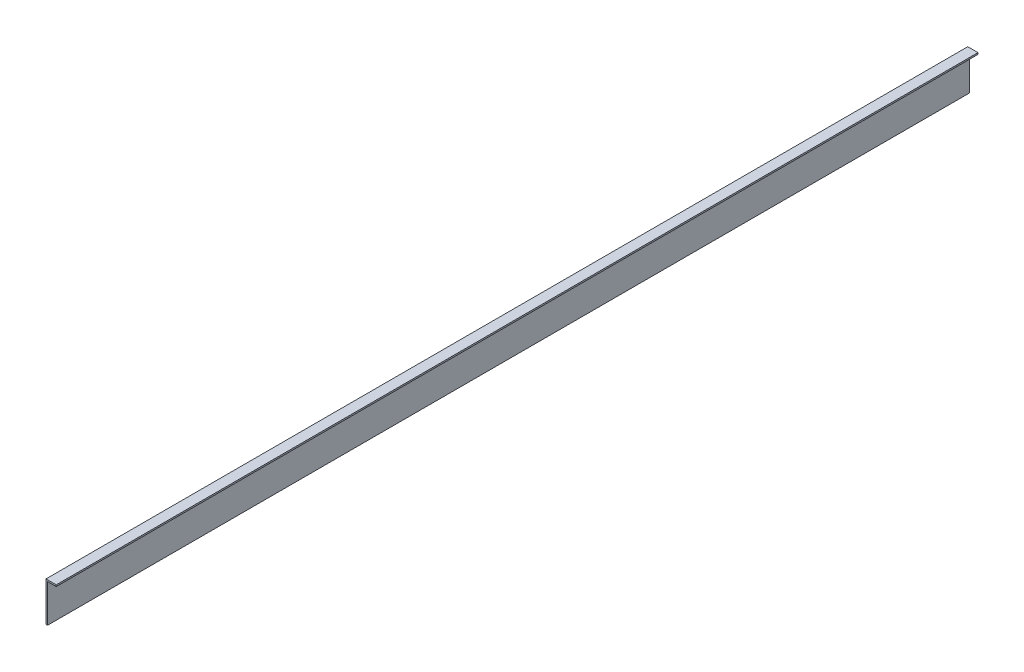
SolidWorks part; units mm, degrees
ref_plane "Front Plane" through (0, 0, 0) normal (0, 0, 1) x (1, 0, 0)
ref_plane "Top Plane" through (0, 0, 0) normal (0, 1, 0) x (1, 0, 0)
ref_plane "Right Plane" through (0, 0, 0) normal (1, 0, 0) x (0, 0, -1)
sketch "Sketch1" plane through (0, 0, 0) normal (0, 0, 1) x (1, 0, 0)
  line L0 (0, 0) -> (0, 38.5)
  line L1 (0, 38.5) -> (10, 38.5)
  line L2 (10, 38.5) -> (10, 37)
  line L3 (10, 37) -> (1.5, 37)
  line L4 (1.5, 37) -> (1.5, 0)
  line L5 (1.5, 0) -> (0, 0)
  dimension "D1" = 10
  dimension "D2" = 1.5
  dimension "D3" = 1.5
  dimension "D4" = 38.5
extrude "Boss-Extrude1" add sketch "Sketch1" against normal blind 900
